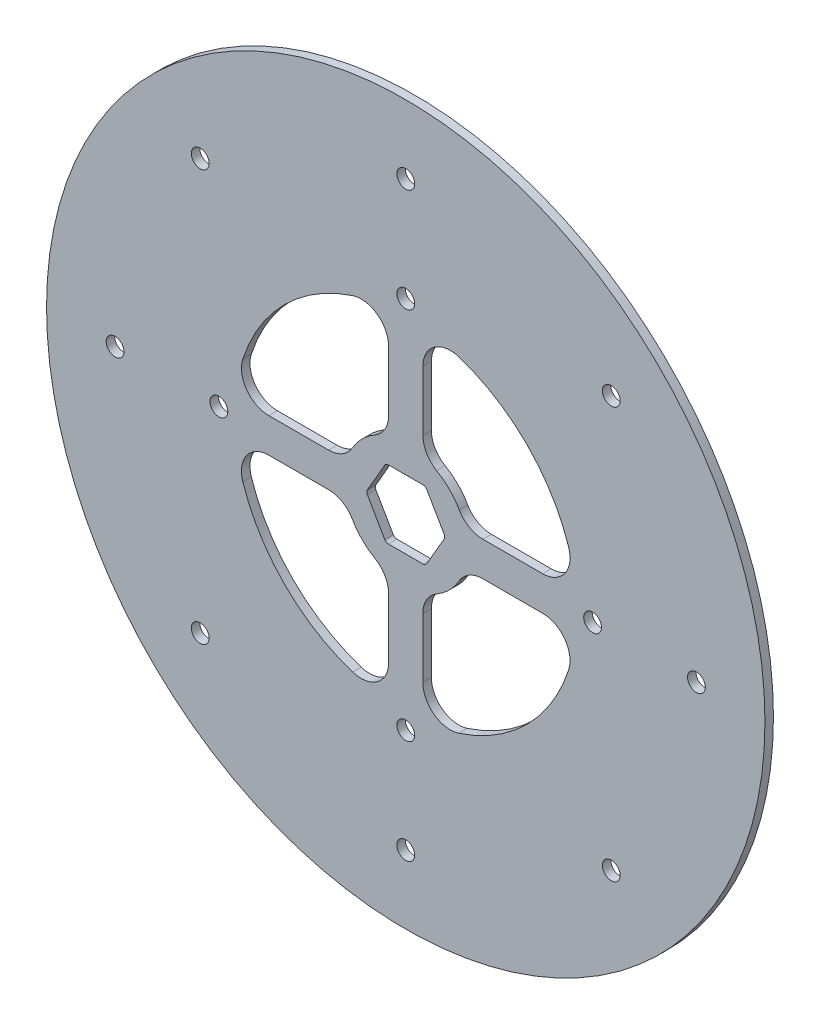
SolidWorks part; units mm, degrees
material "Stainless Steel (ferritic)"
ref_plane "Front Plane" through (0, 0, 0) normal (0, 0, 1) x (1, 0, 0)
ref_plane "Top Plane" through (0, 0, 0) normal (0, 1, 0) x (1, 0, 0)
ref_plane "Right Plane" through (0, 0, 0) normal (1, 0, 0) x (0, 0, -1)
sketch "Sketch1" plane through (0, 0, 0) normal (0, 0, 1) x (1, 0, 0)
  line L0 (0, 0) -> (112.8361, 0) construction
  line L1 (0, -1000) -> (0, 49000) construction
  line L2 (25.3603, 3.175) -> (14.2981, 3.175)
  line L3 (3.175, 25.3603) -> (3.175, 14.2981)
  line L4 (-3.175, 25.3603) -> (-3.175, 14.2981)
  line L5 (3.175, -25.3603) -> (3.175, -14.2981)
  line L7 (-25.3603, 3.175) -> (-14.2981, 3.175)
  line L8 (25.3603, -3.175) -> (14.2981, -3.175)
  line L9 (7.3323, 0) -> (3.6662, 6.35)
  line L10 (-25.3603, -3.175) -> (-14.2981, -3.175)
  line L11 (-3.175, -25.3603) -> (-3.175, -14.2981)
  line L12 (3.6662, 6.35) -> (-3.6662, 6.35)
  line L13 (-3.6662, 6.35) -> (-7.3323, 0)
  line L14 (-7.3323, 0) -> (-3.6662, -6.35)
  line L15 (-3.6662, -6.35) -> (3.6662, -6.35)
  line L16 (3.6662, -6.35) -> (7.3323, 0)
  circle A0 centre (0, 0) radius 66.548
  circle A1 centre (0, 0) radius 11.43 construction
  arc A2 (-31.5909, -3.175) -> (3.175, 31.5909) centre (0, 0) ccw construction
  arc A3 (-10.9802, -3.175) -> (3.175, 10.9802) centre (0, 0) ccw construction
  arc A5 (-5.715, 9.8987) -> (-9.8987, 5.715) centre (0, 0) ccw
  arc A6 (-9.8274, 30.1908) -> (-30.1908, 9.8274) centre (0, 0) ccw
  arc A7 (-5.715, 9.8987) -> (-3.175, 14.2981) centre (-8.255, 14.2981) ccw
  arc A8 (-14.2981, 3.175) -> (-9.8987, 5.715) centre (-14.2981, 8.255) ccw
  arc A9 (-9.8274, 30.1908) -> (-3.175, 25.3603) centre (-8.255, 25.3603) cw
  arc A10 (-30.1908, 9.8274) -> (-25.3603, 3.175) centre (-25.3603, 8.255) ccw
  arc A11 (9.8987, 5.715) -> (5.715, 9.8987) centre (0, 0) ccw
  arc A12 (30.1908, 9.8274) -> (9.8274, 30.1908) centre (0, 0) ccw
  arc A13 (9.8987, 5.715) -> (14.2981, 3.175) centre (14.2981, 8.255) ccw
  arc A14 (3.175, 14.2981) -> (5.715, 9.8987) centre (8.255, 14.2981) ccw
  arc A15 (30.1908, 9.8274) -> (25.3603, 3.175) centre (25.3603, 8.255) cw
  arc A16 (9.8274, 30.1908) -> (3.175, 25.3603) centre (8.255, 25.3603) ccw
  arc A17 (5.715, -9.8987) -> (9.8987, -5.715) centre (0, 0) ccw
  arc A18 (9.8274, -30.1908) -> (30.1908, -9.8274) centre (0, 0) ccw
  arc A19 (5.715, -9.8987) -> (3.175, -14.2981) centre (8.255, -14.2981) ccw
  arc A20 (14.2981, -3.175) -> (9.8987, -5.715) centre (14.2981, -8.255) ccw
  arc A21 (9.8274, -30.1908) -> (3.175, -25.3603) centre (8.255, -25.3603) cw
  arc A22 (30.1908, -9.8274) -> (25.3603, -3.175) centre (25.3603, -8.255) ccw
  arc A23 (-9.8987, -5.715) -> (-5.715, -9.8987) centre (0, 0) ccw
  arc A24 (-30.1908, -9.8274) -> (-9.8274, -30.1908) centre (0, 0) ccw
  arc A25 (-9.8987, -5.715) -> (-14.2981, -3.175) centre (-14.2981, -8.255) ccw
  arc A26 (-3.175, -14.2981) -> (-5.715, -9.8987) centre (-8.255, -14.2981) ccw
  arc A27 (-30.1908, -9.8274) -> (-25.3603, -3.175) centre (-25.3603, -8.255) cw
  arc A28 (-9.8274, -30.1908) -> (-3.175, -25.3603) centre (-8.255, -25.3603) ccw
  circle A29 centre (0, 53.848) radius 1.651
  circle A30 centre (0, 34.6196) radius 1.651
  circle A31 centre (0, 0) radius 6.35 construction
  circle A32 centre (34.6196, 0) radius 1.651
  circle A34 centre (0, -34.6196) radius 1.651
  circle A36 centre (-34.6196, 0) radius 1.651
  circle A39 centre (38.0763, 38.0763) radius 1.651
  circle A40 centre (0, 0) radius 53.848 construction
  circle A41 centre (53.848, 0) radius 1.651
  circle A42 centre (38.0763, -38.0763) radius 1.651
  circle A43 centre (0, -53.848) radius 1.651
  circle A44 centre (-38.0763, -38.0763) radius 1.651
  circle A45 centre (-53.848, 0) radius 1.651
  circle A46 centre (-38.0763, 38.0763) radius 1.651
  circle A47 centre (-53.848, 0) radius 1.651 [skipped]
  circle A48 centre (0, -53.848) radius 1.651 [skipped]
  circle A49 centre (53.848, 0) radius 1.651 [skipped]
  point P15 (-3.175, 10.9802)
  point P23 (-10.9802, 3.175)
  point P26 (-3.175, 31.5909)
  point P68 (0, 0)
  point P85 (0, 0)
  point P108 (0, 0)
  dimension "D1" = 63.5
  dimension "D6" = 5.08
  dimension "D7" = 5.08
  dimension "D9" = 4
  dimension "D10" = 12.7
  dimension "D11" = 133.096
  dimension "D13" = 3.302
  dimension "D14" = 3.302
  dimension "D15" = 12.7
  dimension "D4" = 6.35
  dimension "D5" = 6.35
  dimension "D8" = 4
  dimension "D12" = 8
extrude "Boss-Extrude1" add sketch "Sketch1" along normal blind 1.5748
fillet "Fillet6" radius 0.762 6 edges at (3.6662, 6.35, 0.7874) (7.3323, 0, 0.7874) (3.6662, -6.35, 0.7874) (-3.6662, -6.35, 0.7874) (-7.3323, 0, 0.7874) (-3.6662, 6.35, 0.7874)
